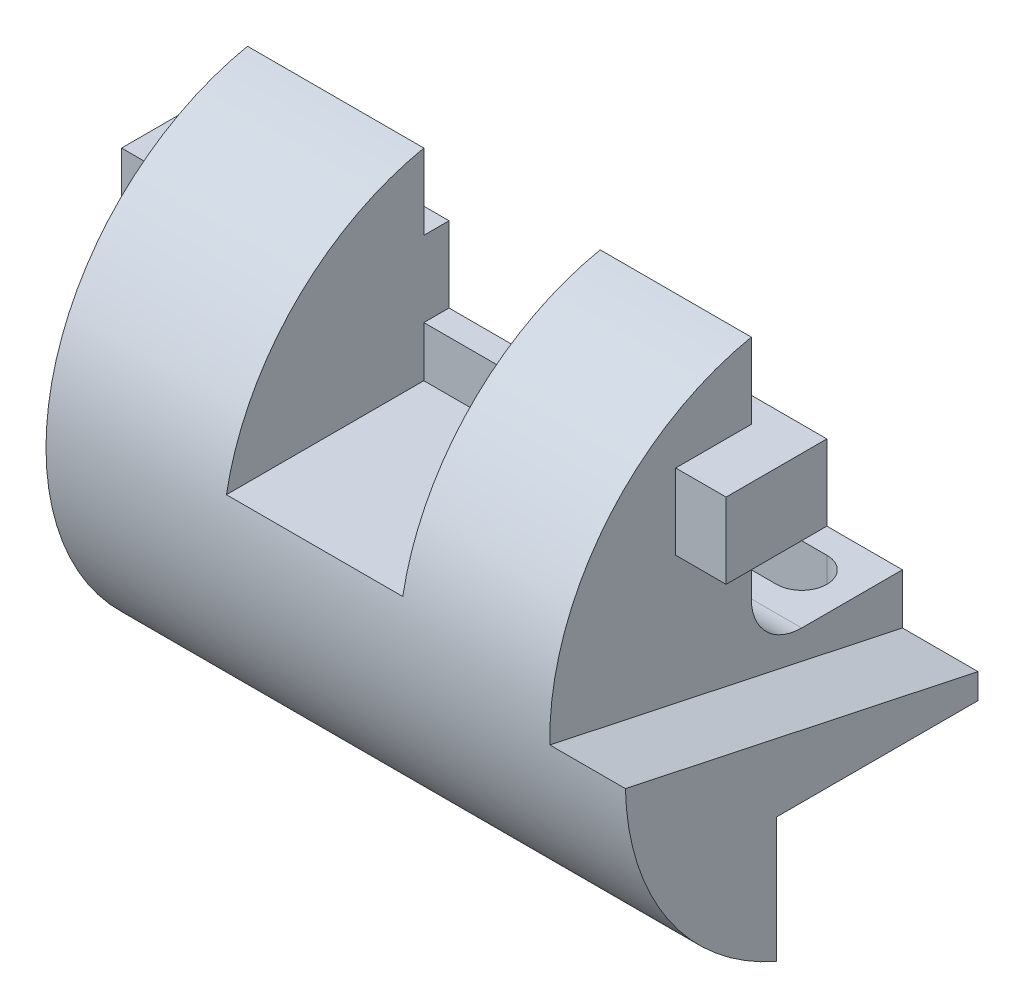
SolidWorks part; units mm, degrees
material "1060 Alloy"
ref_plane "Front Plane" through (0, 0, 0) normal (0, 0, 1) x (1, 0, 0)
ref_plane "Top Plane" through (0, 0, 0) normal (0, 1, 0) x (1, 0, 0)
ref_plane "Right Plane" through (0, 0, 0) normal (1, 0, 0) x (0, 0, -1)
sketch "Sketch1" plane through (0, 0, 0) normal (1, 0, 0) x (0, 0, -1)
  line L0 (0, -79.524) -> (0, 79.524) construction
  line L1 (0, 79.524) -> (0, 0) construction
  line L2 (-86.1633, 0) -> (86.1633, 0) construction
  line L3 (-10, 48.9898) -> (-10, 3.9898)
  line L4 (0, -6.0102) -> (20, -6.0102)
  line L5 (20, -6.0102) -> (20, -21.0102)
  line L6 (20, -21.0102) -> (-20, -21.0102)
  line L7 (-20, -21.0102) -> (-20, -45.8258)
  line L8 (20, -6.0102) -> (20, 3.9898) construction
  arc A0 (-10, 48.9898) -> (-20, -45.8258) centre (0, 0) ccw
  arc A1 (0, -6.0102) -> (-10, 3.9898) centre (0, 3.9898) cw
  point P4 (0, 0)
  point P9 (0, 0)
  point P17 (-10, -6.0102)
  dimension "D1" = 100
  dimension "D7" = 10
  dimension "D2" = 10
  dimension "D3" = 20
  dimension "D4" = 55
  dimension "D5" = 20
  dimension "D6" = 15
extrude "Boss-Extrude1" add sketch "Sketch1" along normal blind 115
sketch "Sketch2" plane through (115, 0, 0) normal (1, 0, 0) x (0, 0, -1)
  line L0 (20, -16.0102) -> (-49.9871, -1.134)
  line L1 (20, -21.0102) -> (20, -6.0102) construction
  line L2 (-10, 48.9898) -> (-10, 3.9898)
  line L3 (0, -6.0102) -> (20, -6.0102)
  line L4 (20, -6.0102) -> (20, -16.0102)
  arc A0 (-10, 48.9898) -> (-20, -45.8258) centre (0, 0) ccw construction
  arc A1 (-49.9871, -1.134) -> (-10, 48.9898) centre (0, 0) cw
  arc A2 (-10, 3.9898) -> (0, -6.0102) centre (0, 3.9898) ccw
  dimension "D3" = 50
  dimension "D1" = 5
  dimension "D2" = 78
extrude "Cut-Extrude3" cut sketch "Sketch2" against normal blind 15
sketch "Sketch4" plane through (0, -6.0102, 0) normal (0, 1, 0) x (1, 0, 0)
  line L0 (10, 10) -> (90, 10) construction
  line L1 (10, 15) -> (90, 15)
  line L2 (10, 5) -> (90, 5)
  line L3 (100, 20) -> (100, 0) construction
  line L6 (100, 20) -> (0, 20) construction
  arc A0 (10, 15) -> (10, 5) centre (10, 10) ccw
  arc A1 (90, 5) -> (90, 15) centre (90, 10) ccw
  point P2 (50, 10)
  point P9 (-13.1488, 69.8457)
  dimension "D1" = 80
  dimension "D2" = 10
  dimension "D3" = 10
  dimension "D4" = 10
extrude "Cut-Extrude4" cut sketch "Sketch4" against normal blind 67
sketch "Sketch5" plane through (0, 0, 10) normal (0, 0, -1) x (-1, 0, 0)
  line L0 (-100, 48.9898) -> (0, 48.9898) construction
  line L1 (-70, 48.9898) -> (-35, 48.9898)
  line L2 (-70, 48.9898) -> (-70, 8.9898)
  line L3 (-70, 8.9898) -> (-35, 8.9898)
  line L4 (-35, 48.9898) -> (-35, 8.9898)
  point P6 (-68.25, 48.9898)
  point P7 (-28.9941, 48.9898)
  point P10 (-114.4441, 65.1622)
  dimension "D1" = 35
  dimension "D2" = 30
  dimension "D3" = 40
extrude "Cut-Extrude5" cut sketch "Sketch5" against normal blind 67
sketch "Sketch6" plane through (0, 0, 10) normal (0, 0, -1) x (-1, 0, 0)
  line L0 (-35, 8.9898) -> (-35, 48.9898) construction
  line L1 (-35, 33.9898) -> (5, 33.9898)
  line L2 (-35, 33.9898) -> (-35, 18.9898)
  line L3 (-35, 18.9898) -> (5, 18.9898)
  line L4 (5, 33.9898) -> (5, 18.9898)
  point P7 (-35, 26.4898)
  dimension "D1" = 40
  dimension "D2" = 10
  dimension "D3" = 15
extrude "Boss-Extrude2" add sketch "Sketch6" along normal blind 5
sketch "Sketch7" plane through (0, 0, 0) normal (-1, 0, 0) x (0, 0, 1)
  line L1 (10, 33.9898) -> (25, 33.9898)
  line L2 (10, 33.9898) -> (10, 18.9898)
  line L3 (10, 18.9898) -> (25, 18.9898)
  line L4 (25, 33.9898) -> (25, 18.9898)
  dimension "D1" = 15
  dimension "D2" = 15
extrude "Boss-Extrude4" add sketch "Sketch7" along normal blind 10
sketch "Sketch8" plane through (0, 0, 10) normal (0, 0, -1) x (-1, 0, 0)
  line L1 (5, 33.9898) -> (10, 33.9898)
  line L2 (5, 33.9898) -> (5, 18.9898)
  line L3 (5, 18.9898) -> (10, 18.9898)
  line L4 (10, 33.9898) -> (10, 18.9898)
extrude "Boss-Extrude5" add sketch "Sketch8" along normal blind 5
sketch "Sketch9" plane through (0, 0, 10) normal (0, 0, -1) x (-1, 0, 0)
  line L0 (-70, 48.9898) -> (-70, 8.9898) construction
  line L1 (-70, 33.9898) -> (-110, 33.9898)
  line L2 (-70, 33.9898) -> (-70, 18.9898)
  line L3 (-70, 18.9898) -> (-110, 18.9898)
  line L4 (-110, 33.9898) -> (-110, 18.9898)
  dimension "D1" = 40
  dimension "D2" = 10
  dimension "D3" = 15
extrude "Boss-Extrude6" add sketch "Sketch9" along normal blind 5 and the other way blind 15
